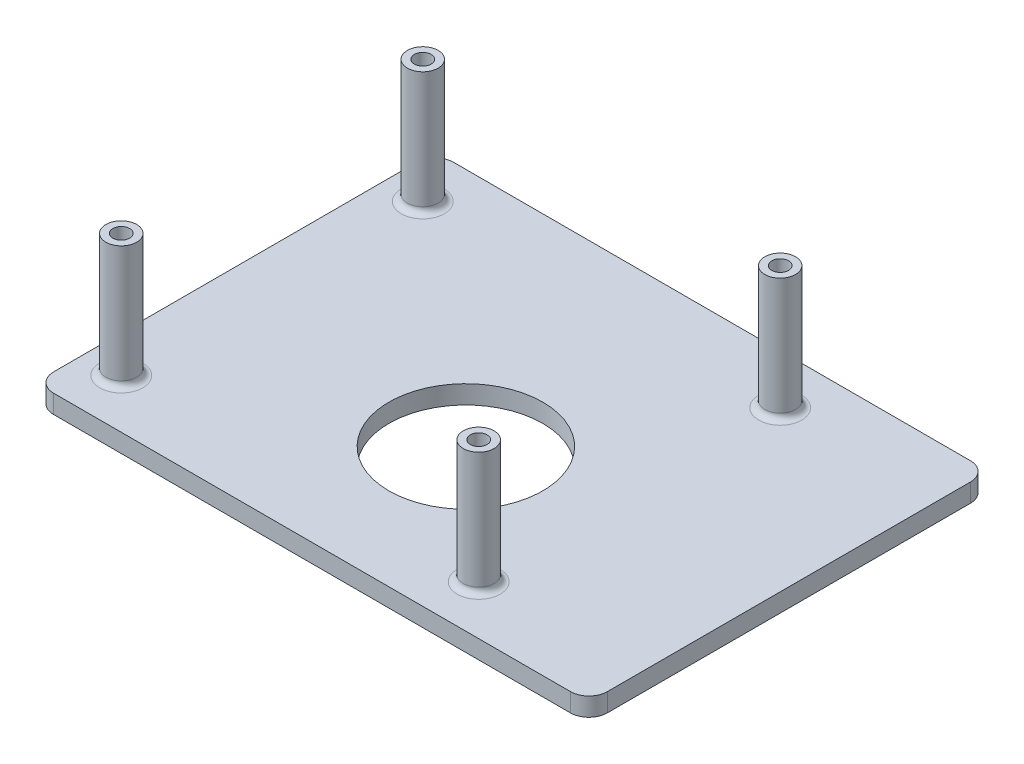
SolidWorks part; units mm, degrees
ref_plane "Front" through (0, 0, 0) normal (0, 0, 1) x (1, 0, 0)
ref_plane "Top" through (0, 0, 0) normal (0, 1, 0) x (1, 0, 0)
ref_plane "Right" through (0, 0, 0) normal (1, 0, 0) x (0, 0, -1)
sketch "Skizze1" plane through (0, 0, 0) normal (0, 1, 0) x (1, 0, 0)
  line L0 (-45, -32.5) -> (-45, 32.5)
  line L1 (-45, -32.5) -> (45, -32.5)
  line L2 (-45, 32.5) -> (45, 32.5)
  line L3 (45, -32.5) -> (45, 32.5)
  line L4 (-45, -32.5) -> (45, 32.5) construction
  line L5 (-45, 32.5) -> (45, -32.5) construction
  point P1 (0, 0)
  dimension "D1" = 90
  dimension "D2" = 65
extrude "Aufsatz-Linear austragen1" add sketch "Skizze1" along normal blind 3
sketch "Skizze3" plane through (0, 3, 0) normal (0, 1, 0) x (1, 0, 0)
  circle A0 centre (-39, 24.5) radius 2.5
  circle A1 centre (19.0855, 24.5) radius 2.5
  circle A2 centre (19.0855, -24.5) radius 2.5
  circle A3 centre (-39, -24.5) radius 2.5
  dimension "D1" = 5
extrude "Aufsatz-Linear austragen2" add sketch "Skizze3" along normal blind 20
sketch "Skizze4" plane through (0, 23, 0) normal (0, 1, 0) x (1, 0, 0)
  circle A0 centre (19.0855, 24.5) radius 1.3645 construction
  circle A3 centre (-39, 24.5) radius 1.3645 construction
  circle A4 centre (-39, -24.5) radius 1.3645 construction
  circle A5 centre (19.0855, -24.5) radius 1.3645 construction
  circle A6 centre (19.0855, 24.5) radius 1.3645
  circle A7 centre (-39, 24.5) radius 1.3645
  circle A8 centre (-39, -24.5) radius 1.3645
  circle A9 centre (19.0855, -24.5) radius 1.3645
extrude "Schnitt-Linear austragen2" cut sketch "Skizze4" against normal through all
fillet "Verrundung1" radius 3 4 edges at (45, 1.5, -32.5) (-45, 1.5, -32.5) (-45, 1.5, 32.5) (45, 1.5, 32.5)
fillet "Verrundung2" radius 1 4 edges at (-39, 3, 27) (19.0855, 3, 27) (19.0855, 3, -22) (-39, 3, -22)
sketch "Skizze5" plane through (0, 0, 0) normal (0, -1, 0) x (1, 0, 0)
  circle A0 centre (-1, 6.5) radius 12.5003
  circle A2 centre (-39, 24.5) radius 1.3645 construction
  point P2 (-11.5469, 0)
  dimension "D1" = 18
  dimension "D3" = 25.0007
  dimension "D2" = 38
extrude "Schnitt-Linear austragen3" cut sketch "Skizze5" against normal through all
